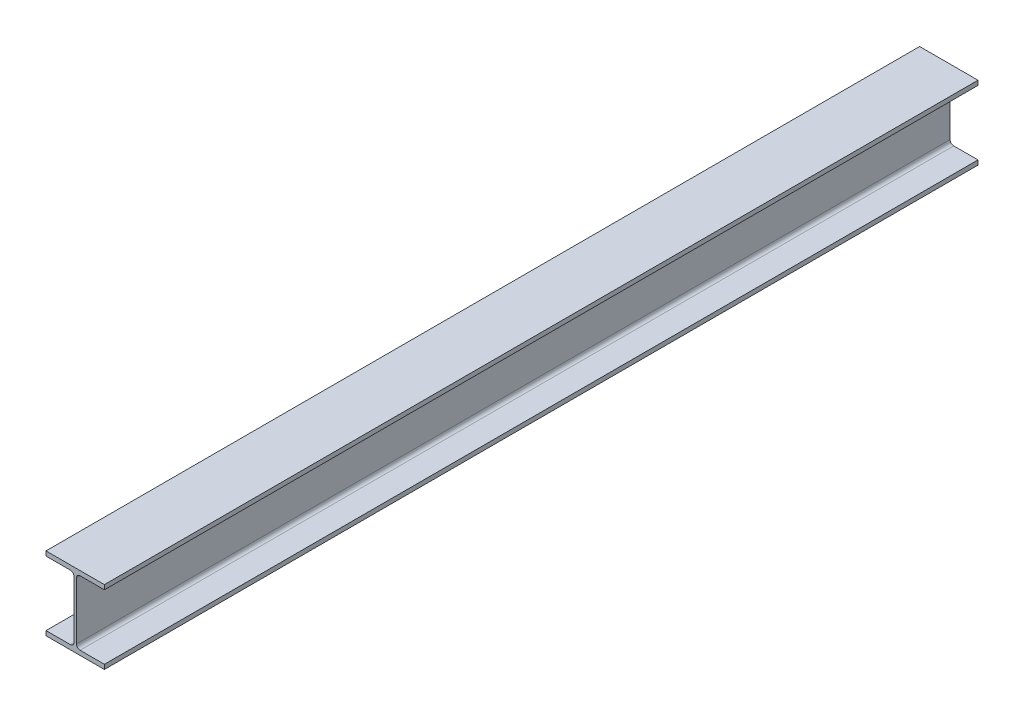
SolidWorks part; units mm, degrees
ref_plane "Plane1" through (0, 0, 0) normal (0, 0, 1) x (1, 0, 0)
ref_plane "Plane2" through (0, 0, 0) normal (0, 1, 0) x (1, 0, 0)
ref_plane "Plane3" through (0, 0, 0) normal (1, 0, 0) x (0, 0, -1)
sketch "Sketch1" plane through (0, 0, 0) normal (0, 0, 1) x (1, 0, 0)
  line L0 (0, 0) -> (0, 15.748)
  line L1 (0, 15.748) -> (84.709, 15.748)
  line L2 (97.409, 28.448) -> (97.409, 228.092)
  line L3 (84.709, 240.792) -> (0, 240.792)
  line L4 (0, 240.792) -> (0, 256.54)
  line L5 (0, 256.54) -> (203.708, 256.54)
  line L6 (203.708, 256.54) -> (203.708, 240.792)
  line L7 (203.708, 240.792) -> (118.999, 240.792)
  line L8 (106.299, 228.092) -> (106.299, 28.448)
  line L9 (118.999, 15.748) -> (203.708, 15.748)
  line L10 (203.708, 15.748) -> (203.708, 0)
  line L11 (203.708, 0) -> (0, 0)
  line L12 (101.854, -72.1361) -> (101.854, 256.54) construction
  arc A0 (84.709, 15.748) -> (97.409, 28.448) centre (84.709, 28.448) ccw
  arc A1 (97.409, 228.092) -> (84.709, 240.792) centre (84.709, 228.092) ccw
  arc A2 (118.999, 240.792) -> (106.299, 228.092) centre (118.999, 228.092) ccw
  arc A3 (106.299, 28.448) -> (118.999, 15.748) centre (118.999, 28.448) ccw
  dimension "Ri" = 12.7
  dimension "Tw" = 8.89
  dimension "Bf" = 203.708
  dimension "Depth" = 256.54
  dimension "Tf" = 15.748
  dimension "D2" = 15.748
  dimension "D1" = 4.445
extrude "BaseSteelW" add sketch "Sketch1" against normal mid plane 3048
equation "\"D1@Sketch1\" = \"Tw@Sketch1\" / 2"
equation "\"D2@Sketch1\" = \"Tf@Sketch1\""
